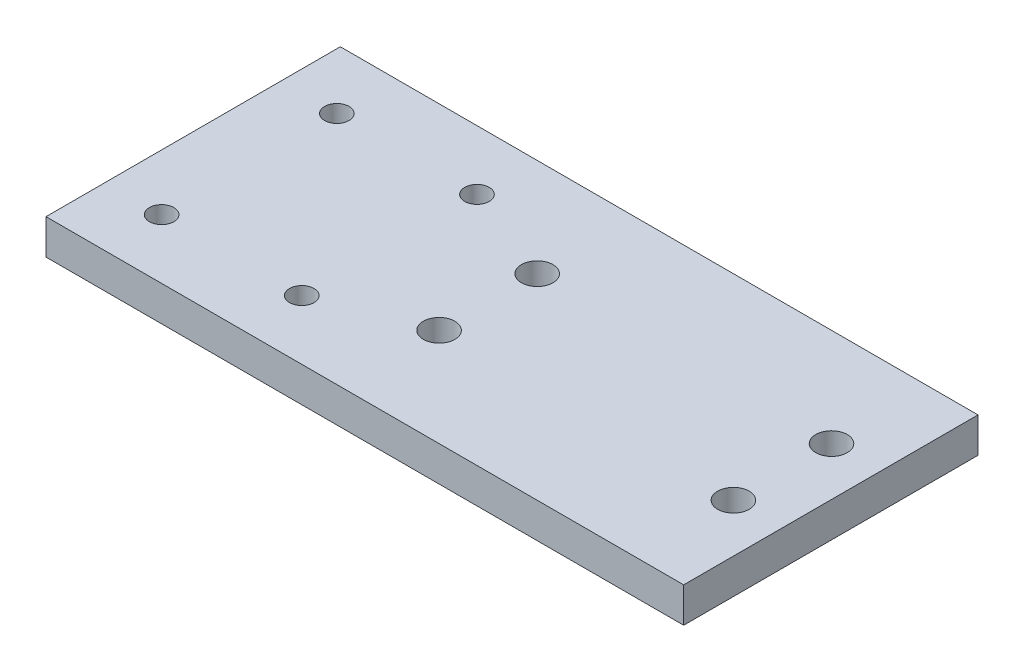
SolidWorks part; units mm, degrees
ref_plane "정면" through (0, 0, 0) normal (0, 0, 1) x (1, 0, 0)
ref_plane "윗면" through (0, 0, 0) normal (0, 1, 0) x (1, 0, 0)
ref_plane "우측면" through (0, 0, 0) normal (1, 0, 0) x (0, 0, -1)
sketch "스케치1" plane through (0, 0, 0) normal (0, 1, 0) x (1, 0, 0)
  line L1 (0, 0) -> (91, 0)
  line L2 (0, 0) -> (0, 42)
  line L3 (0, 42) -> (91, 42)
  line L4 (91, 0) -> (91, 42)
  dimension "D1" = 91
  dimension "D2" = 42
extrude "보스-돌출1" add sketch "스케치1" along normal blind 5
sketch "스케치2" plane through (0, 5, 0) normal (0, 1, 0) x (1, 0, 0)
  line L0 (0, 42) -> (0, 0) construction
  line L1 (8, 33.5) -> (28, 33.5) construction
  line L2 (8, 33.5) -> (8, 8.5) construction
  line L3 (8, 8.5) -> (28, 8.5) construction
  line L4 (28, 33.5) -> (28, 8.5) construction
  line L5 (91, 42) -> (0, 42) construction
  line L7 (84.0949, 28) -> (84.0949, 42) construction
  line L8 (42.0949, 28) -> (84.0949, 28) construction
  line L9 (42.0949, 28) -> (42.0949, 14) construction
  line L10 (42.0949, 14) -> (84.0949, 14) construction
  line L11 (84.0949, 28) -> (84.0949, 14) construction
  line L12 (84.0949, 14) -> (84.0949, 0) construction
  line L13 (0, 0) -> (91, 0) construction
  line L14 (91, 21) -> (78, 21) construction
  line L15 (91, 0) -> (91, 42) construction
  line L16 (78, 21) -> (13, 21) construction
  line L17 (13, 21) -> (0, 21) construction
  circle A0 centre (28, 33.5) radius 1.75
  circle A1 centre (28, 8.5) radius 1.75
  circle A2 centre (8, 8.5) radius 1.75
  circle A3 centre (8, 33.5) radius 1.75
  circle A4 centre (42.0949, 28) radius 2.25
  circle A5 centre (42.0949, 14) radius 2.25
  circle A6 centre (84.0949, 14) radius 2.25
  circle A7 centre (84.0949, 28) radius 2.25
  circle A8 centre (78, 21) radius 1.9 construction
  circle A9 centre (13, 21) radius 1.9 construction
  dimension "D5" = 3.5
  dimension "D8" = 4.5
  dimension "D10" = 3.8
  dimension "D1" = 8
  dimension "D2" = 8.5
  dimension "D3" = 25
  dimension "D4" = 20
  dimension "D6" = 14
  dimension "D7" = 42
  dimension "D9" = 65
extrude "컷-돌출1" cut sketch "스케치2" against normal blind 5
sketch "스케치3" plane through (0, 5, 0) normal (0, 1, 0) x (1, 0, 0)
  circle A0 centre (84.0949, 28) radius 4
  circle A1 centre (84.0949, 14) radius 4
  circle A2 centre (42.0949, 14) radius 4
  circle A3 centre (42.0949, 28) radius 4
  circle A4 centre (28, 33.5) radius 3.25
  circle A5 centre (28, 8.5) radius 3.25
  circle A6 centre (8, 8.5) radius 3.25
  circle A7 centre (8, 33.5) radius 3.25
  dimension "D1" = 8
  dimension "D2" = 6.5
extrude "컷-돌출2" [suppressed] cut sketch "스케치3" against normal blind 5
